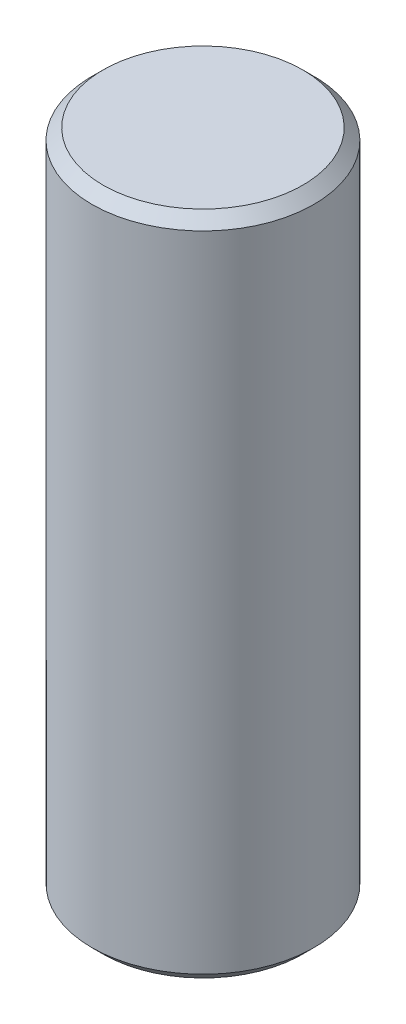
SolidWorks part; units mm, degrees
material "AISI 1015 Steel, Cold Drawn (SS)"
ref_plane "Front Plane" through (0, 0, 0) normal (0, 0, 1) x (1, 0, 0)
ref_plane "Top Plane" through (0, 0, 0) normal (0, 1, 0) x (1, 0, 0)
ref_plane "Right Plane" through (0, 0, 0) normal (1, 0, 0) x (0, 0, -1)
sketch "Sketch1" plane through (0, 0, 0) normal (0, 1, 0) x (1, 0, 0)
  circle A0 centre (0, 0) radius 20
extrude "Boss-Extrude1" add sketch "Sketch1" along normal blind 120
chamfer "Chamfer1" distance 2 angle 45 2 edges at (0, 0, 20) (0, 120, 20)
